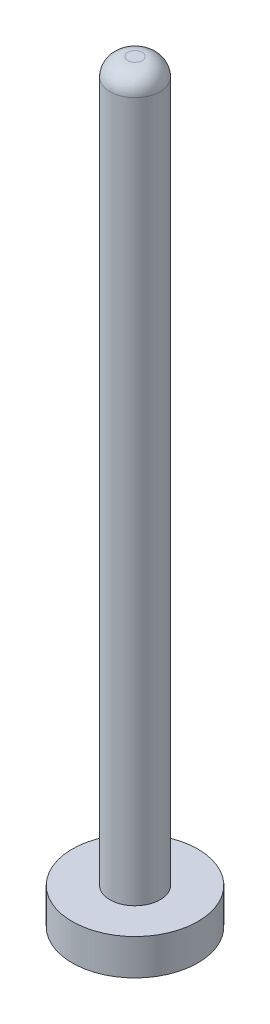
SolidWorks part; units mm, degrees
ref_plane "Front Plane" through (0, 0, 0) normal (0, 0, 1) x (1, 0, 0)
ref_plane "Top Plane" through (0, 0, 0) normal (0, 1, 0) x (1, 0, 0)
ref_plane "Right Plane" through (0, 0, 0) normal (1, 0, 0) x (0, 0, -1)
sketch "Sketch1" plane through (0, 0, 0) normal (0, 1, 0) x (1, 0, 0)
  circle A0 centre (0, 0) radius 1.4
  dimension "D1" = 2.8
extrude "Boss-Extrude1" add sketch "Sketch1" along normal blind 40 contours A0
sketch "Sketch2" plane through (0, 0, 0) normal (0, -1, 0) x (1, 0, 0)
  circle A0 centre (0, 0) radius 3.5
  dimension "D1" = 7
extrude "Boss-Extrude2" add sketch "Sketch2" along normal blind 2
fillet "Fillet2" radius 1 1 edges at (0, 40, 1.4)
